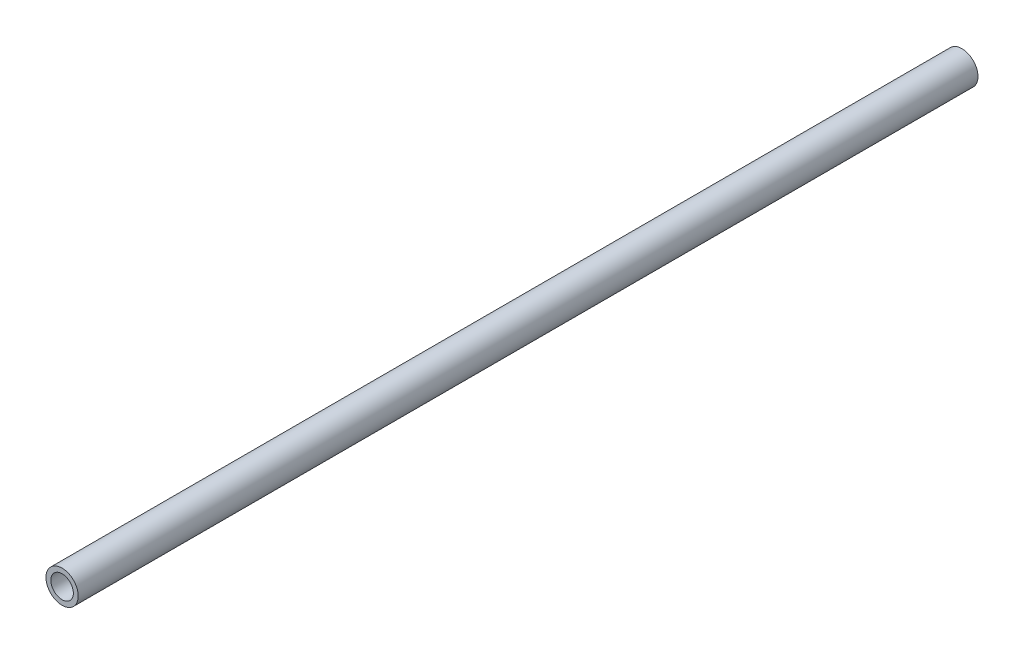
SolidWorks part; units mm, degrees
ref_plane "Front Plane" through (0, 0, 0) normal (0, 0, 1) x (1, 0, 0)
ref_plane "Top Plane" through (0, 0, 0) normal (0, 1, 0) x (1, 0, 0)
ref_plane "Right Plane" through (0, 0, 0) normal (1, 0, 0) x (0, 0, -1)
sketch "Sketch1" plane through (0, 0, 0) normal (0, 0, 1) x (1, 0, 0)
  circle A0 centre (0, 0) radius 7.5
  circle A1 centre (0, 0) radius 10.75
  dimension "D1" = 15
  dimension "D2" = 21.5
extrude "Boss-Extrude1" add sketch "Sketch1" along normal blind 600
